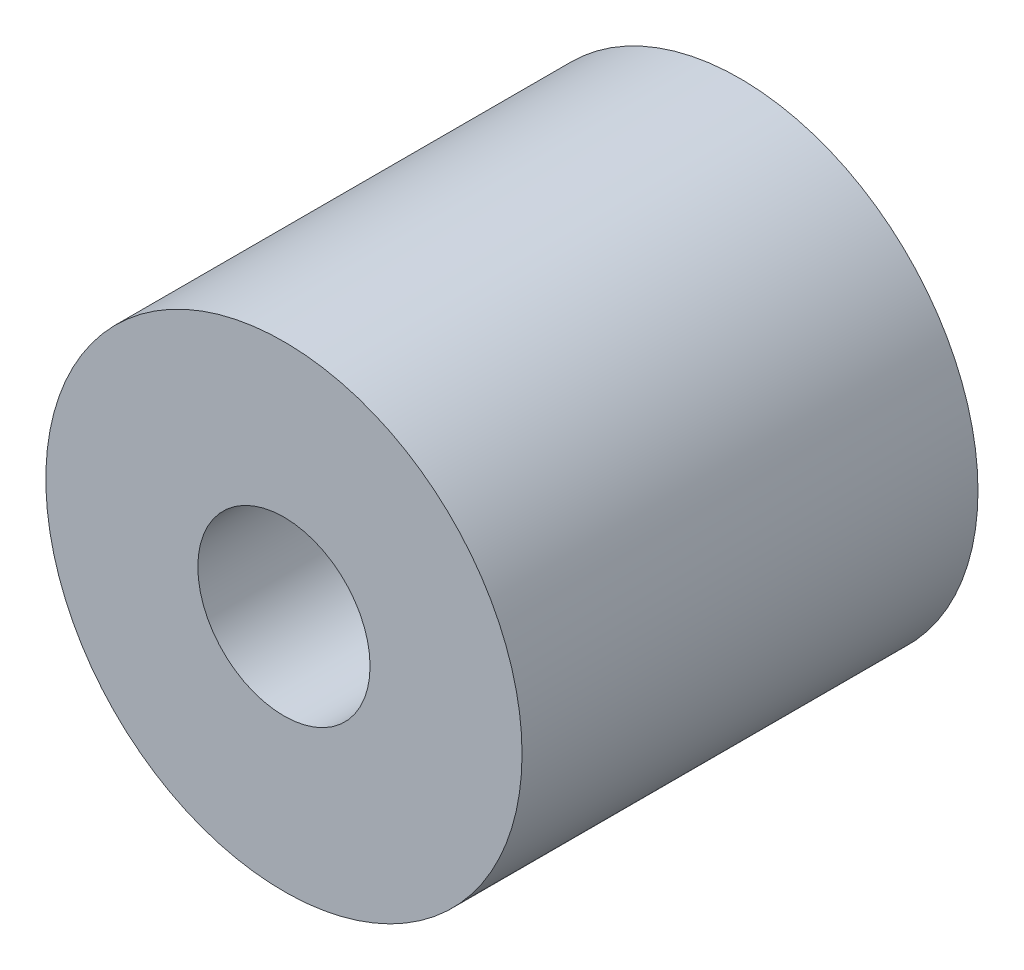
SolidWorks part; units mm, degrees
ref_plane "Front Plane" through (0, 0, 0) normal (0, 0, 1) x (1, 0, 0)
ref_plane "Top Plane" through (0, 0, 0) normal (0, 1, 0) x (1, 0, 0)
ref_plane "Right Plane" through (0, 0, 0) normal (1, 0, 0) x (0, 0, -1)
sketch "Sketch1" plane through (0, 0, 0) normal (0, 0, 1) x (1, 0, 0)
  circle A0 centre (0, 0) radius 1.7
  circle A2 centre (0, 0) radius 4.7
  dimension "D1" = 3.4
  dimension "D2" = 3
extrude "Boss-Extrude1" add sketch "Sketch1" along normal blind 9
